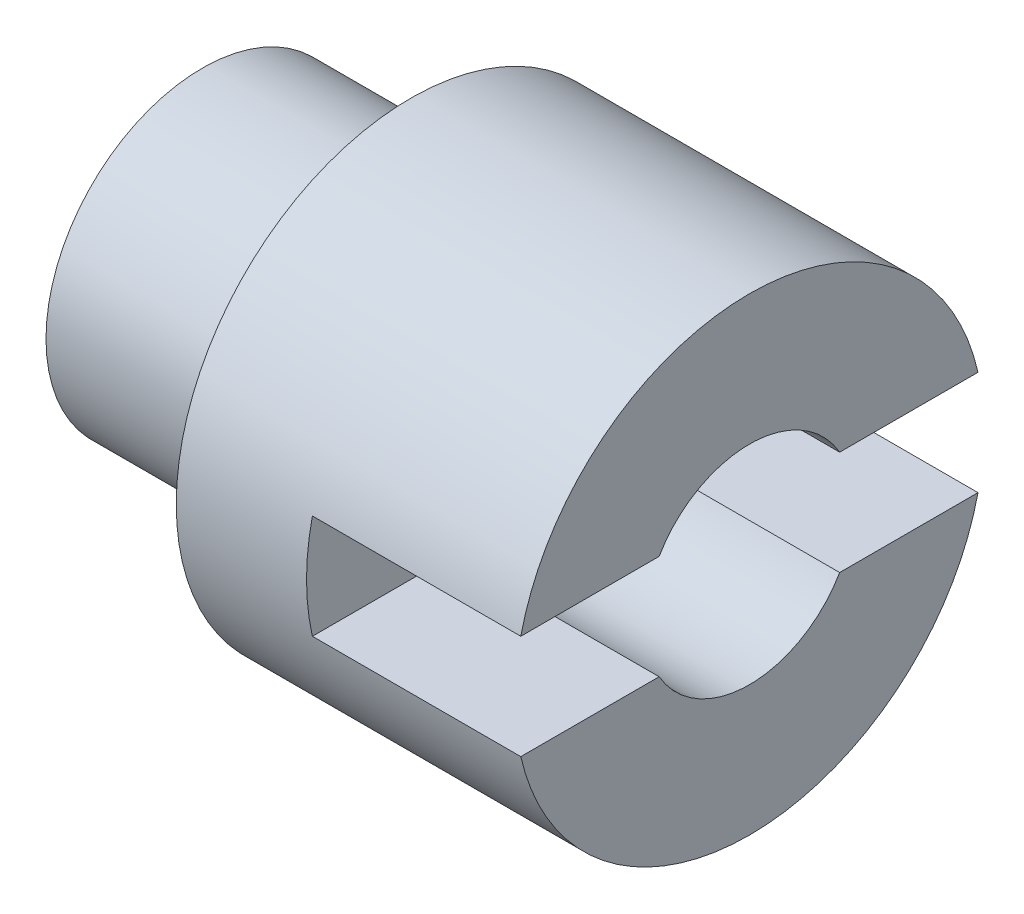
SolidWorks part; units mm, degrees
ref_plane "前视基准面" through (0, 0, 0) normal (0, 0, 1) x (1, 0, 0)
ref_plane "上视基准面" through (0, 0, 0) normal (0, 1, 0) x (1, 0, 0)
ref_plane "右视基准面" through (0, 0, 0) normal (1, 0, 0) x (0, 0, -1)
sketch "草图1" plane through (0, 0, 0) normal (1, 0, 0) x (0, 0, -1)
  circle A0 centre (0, 0) radius 2
  circle A1 centre (0, 0) radius 4.5
  dimension "D1" = 9
  dimension "D2" = 4
extrude "凸台-拉伸1" add sketch "草图1" along normal blind 4
sketch "草图2" plane through (4, 0, 0) normal (1, 0, 0) x (0, 0, -1)
  line L1 (-5.5444, 1) -> (5.3079, 1)
  line L2 (-5.5444, 1) -> (-5.5444, -1)
  line L3 (-5.5444, -1) -> (5.3079, -1)
  line L4 (5.3079, 1) -> (5.3079, -1)
  circle A0 centre (0, 0) radius 2 construction
  dimension "D1" = 2
  dimension "D2" = 1
extrude "切除-拉伸1" cut sketch "草图2" against normal blind 4
sketch "草图5" plane through (0, 0, 0) normal (-1, 0, 0) x (0, 0, 1)
  circle A0 centre (0, 0) radius 4.5
extrude "凸台-拉伸3" add sketch "草图5" along normal blind 2.5
sketch "草图6" plane through (-2.5, 0, 0) normal (-1, 0, 0) x (0, 0, 1)
  circle A0 centre (0, 0) radius 3
  dimension "D1" = 6
extrude "凸台-拉伸4" add sketch "草图6" along normal blind 4
sketch "草图7" plane through (-6.5, 0, 0) normal (-1, 0, 0) x (0, 0, 1)
  circle A0 centre (0, 0) radius 0.98
  dimension "D1" = 1.96
extrude "切除-拉伸2" cut sketch "草图7" against normal through all
